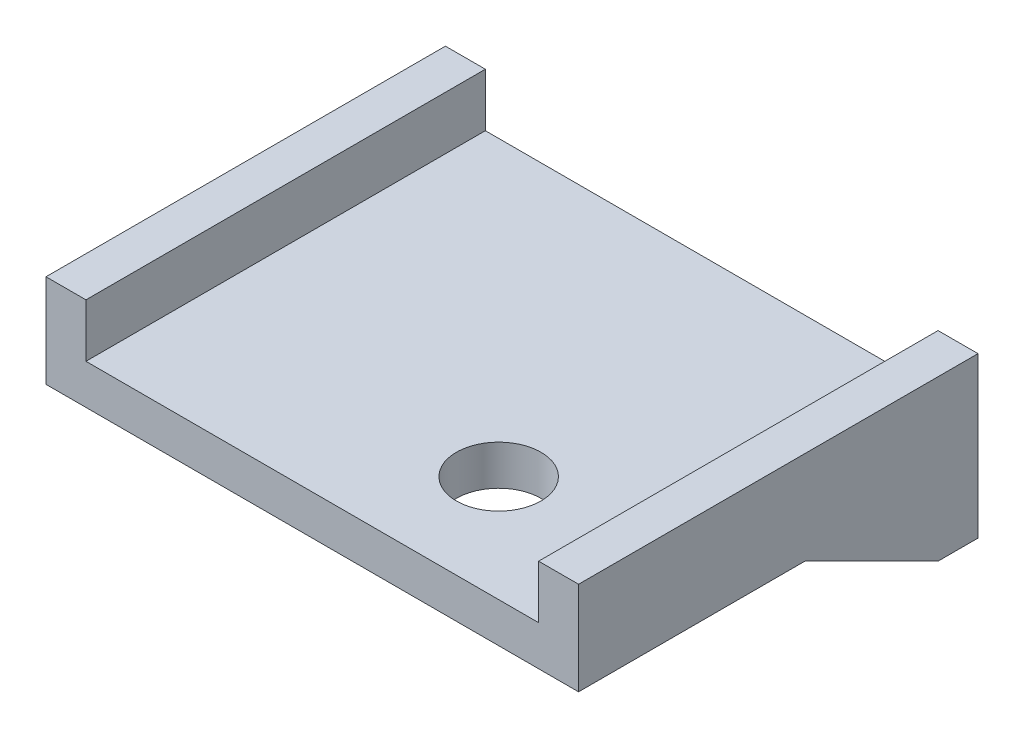
SolidWorks part; units mm, degrees
ref_plane "Front Plane" through (0, 0, 0) normal (0, 0, 1) x (1, 0, 0)
ref_plane "Top Plane" through (0, 0, 0) normal (0, 1, 0) x (1, 0, 0)
ref_plane "Right Plane" through (0, 0, 0) normal (1, 0, 0) x (0, 0, -1)
sketch "Sketch1" plane through (0, 0, 0) normal (0, 1, 0) x (1, 0, 0)
  line L1 (-39.4784, 15.1925) -> (0.5216, 15.1925)
  line L2 (-39.4784, 15.1925) -> (-39.4784, -14.8075)
  line L3 (-39.4784, -14.8075) -> (0.5216, -14.8075)
  line L4 (0.5216, 15.1925) -> (0.5216, -14.8075)
  dimension "D1" = 40
  dimension "D2" = 30
extrude "Boss-Extrude2" add sketch "Sketch1" along normal blind 3
sketch "Sketch2" plane through (0, 3, 0) normal (0, 1, 0) x (1, 0, 0)
  line L0 (-39.4784, -14.8075) -> (0.5216, -14.8075) construction
  line L1 (0.5216, 15.1925) -> (-2.4784, 15.1925)
  line L2 (0.5216, 15.1925) -> (0.5216, -14.8075)
  line L3 (0.5216, -14.8075) -> (-2.4784, -14.8075)
  line L4 (-2.4784, 15.1925) -> (-2.4784, -14.8075)
  dimension "D1" = 3
extrude "Boss-Extrude3" add sketch "Sketch2" along normal blind 4
sketch "Sketch3" plane through (0, 3, 0) normal (0, 1, 0) x (1, 0, 0)
  line L0 (-39.4784, -14.8075) -> (-2.4784, -14.8075) construction
  line L1 (-39.4784, 15.1925) -> (-36.4784, 15.1925)
  line L2 (-39.4784, 15.1925) -> (-39.4784, -14.8075)
  line L3 (-39.4784, -14.8075) -> (-36.4784, -14.8075)
  line L4 (-36.4784, 15.1925) -> (-36.4784, -14.8075)
  dimension "D1" = 3
extrude "Boss-Extrude4" add sketch "Sketch3" along normal blind 4
sketch "Sketch4" plane through (0, 3, 0) normal (0, 1, 0) x (1, 0, 0)
  circle A0 centre (-13.4784, -6.8075) radius 3.175
  dimension "D1" = 26
  dimension "D2" = 22
extrude "Cut-Extrude1" cut sketch "Sketch4" against normal through all
sketch "Sketch5" plane through (0, 0, 0) normal (0, -1, 0) x (-1, 0, 0)
  line L0 (39.4784, 15.1925) -> (39.4784, -14.8075) construction
  line L1 (-0.5216, 15.1925) -> (39.4784, 15.1925)
  line L2 (-0.5216, 15.1925) -> (-0.5216, 12.1925)
  line L3 (-0.5216, 12.1925) -> (39.4784, 12.1925)
  line L4 (39.4784, 15.1925) -> (39.4784, 12.1925)
  dimension "D1" = 3
extrude "Boss-Extrude5" add sketch "Sketch5" along normal blind 5
ref_plane "Plane1" through (0.5216, 0, -12.1925) normal (-1, 0, 0) x (0, 0, 1)
ref_plane "Plane2" through (0.5216, 0, -12.1925) normal (-1, 0, 0) x (0, 0, 1)
sketch "Sketch8" plane through (0.5216, 0, -12.1925) normal (-1, 0, 0) x (0, 0, 1)
  line L0 (0, -5) -> (10, 0)
  line L1 (27, 0) -> (0, 0) construction
  dimension "D1" = 10
rib "Rib4" sketch "Sketch8" sketch "Sketch8" thickness 3 parameters "D1"=3
ref_plane "Plane3" through (-39.4784, 0, -12.1925) normal (-1, 0, 0) x (0, 0, 1)
sketch "Sketch10" plane through (-39.4784, 0, -12.1925) normal (-1, 0, 0) x (0, 0, 1)
  line L0 (0, -5) -> (10, 0)
  line L1 (0, 0) -> (27, 0) construction
  dimension "D1" = 10
rib "Rib5" sketch "Sketch10" sketch "Sketch10" thickness 3 extrusion direction parallel to sketch draft on no parameters "D1"=3
